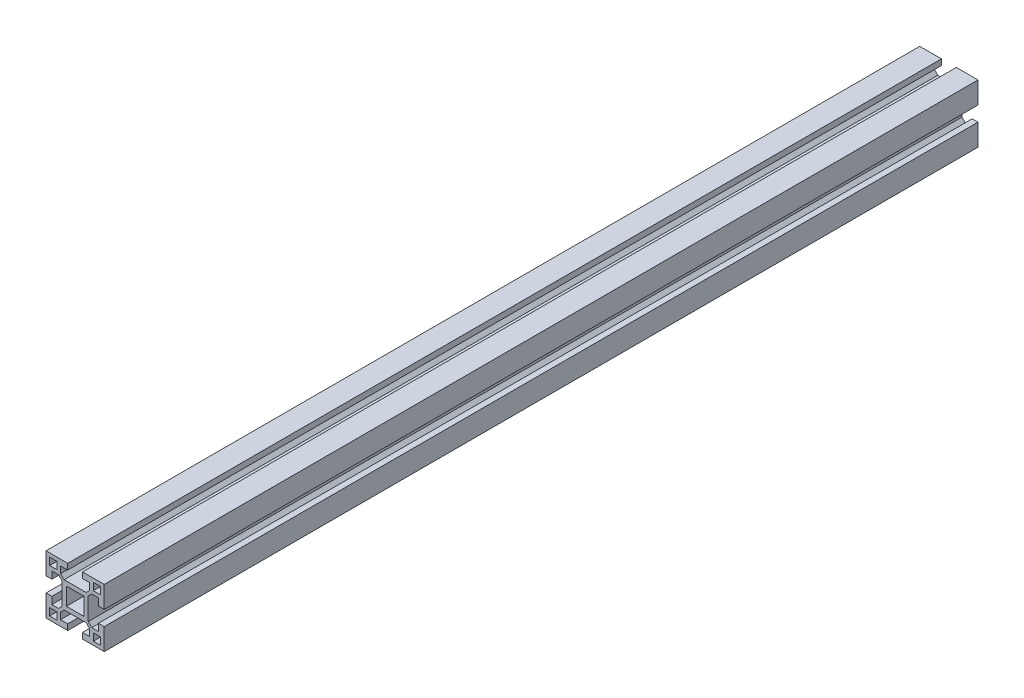
SolidWorks part; units mm, degrees
ref_plane "Plan de face" through (0, 0, 0) normal (0, 0, 1) x (1, 0, 0)
ref_plane "Plan de dessus" through (0, 0, 0) normal (0, 1, 0) x (1, 0, 0)
ref_plane "Plan de droite" through (0, 0, 0) normal (1, 0, 0) x (0, 0, -1)
sketch "Esquisse1" plane through (0, 0, 0) normal (0, 0, 1) x (1, 0, 0)
  line L0 (0, 77.7519) -> (0, -23.3251) construction
  line L1 (17.5, 17.5) -> (12.5, 17.5)
  line L2 (0, 9) -> (7.5858, 9)
  line L3 (0, 6) -> (6, 6)
  line L4 (0, 0) -> (41.9496, 41.9496) construction
  line L5 (7.5858, 9) -> (10, 11.4142)
  line L6 (10, 16) -> (5.1, 16)
  line L7 (5.1, 20) -> (5.1, 16)
  line L8 (12.5, 17.5) -> (12.5, 12.5)
  line L9 (5.1, 20) -> (20, 20)
  line L10 (15, 17.5) -> (15, 15) construction
  line L11 (10, 16) -> (10, 11.4142)
  line L12 (17.5, 15) -> (15, 15) construction
  line L13 (16, 10) -> (11.4142, 10)
  line L14 (20, 5.1) -> (20, 20)
  line L15 (17.5, 12.5) -> (12.5, 12.5)
  line L16 (20, 5.1) -> (16, 5.1)
  line L17 (16, 10) -> (16, 5.1)
  line L18 (9, 7.5858) -> (11.4142, 10)
  line L19 (6, 0) -> (6, 6)
  line L20 (9, 0) -> (9, 7.5858)
  line L21 (17.5, 17.5) -> (17.5, 12.5)
  line L22 (0, -6) -> (6, -6)
  line L23 (0, -9) -> (7.5858, -9)
  line L24 (7.5858, -9) -> (10, -11.4142)
  line L25 (6, 0) -> (6, -6)
  line L26 (9, 0) -> (9, -7.5858)
  line L27 (9, -7.5858) -> (11.4142, -10)
  line L28 (16, -10) -> (11.4142, -10)
  line L29 (16, -10) -> (16, -5.1)
  line L30 (20, -5.1) -> (16, -5.1)
  line L31 (20, -5.1) -> (20, -20)
  line L32 (17.5, -12.5) -> (12.5, -12.5)
  line L33 (17.5, -17.5) -> (17.5, -12.5)
  line L34 (17.5, -17.5) -> (12.5, -17.5)
  line L35 (10, -16) -> (10, -11.4142)
  line L36 (10, -16) -> (5.1, -16)
  line L37 (5.1, -20) -> (5.1, -16)
  line L38 (5.1, -20) -> (20, -20)
  line L39 (12.5, -17.5) -> (12.5, -12.5)
  line L40 (-6, 0) -> (-6, -6)
  line L41 (-9, 0) -> (-9, -7.5858)
  line L42 (-9, -7.5858) -> (-11.4142, -10)
  line L43 (0, -6) -> (-6, -6)
  line L44 (0, -9) -> (-7.5858, -9)
  line L45 (-7.5858, -9) -> (-10, -11.4142)
  line L46 (-10, -16) -> (-10, -11.4142)
  line L47 (-10, -16) -> (-5.1, -16)
  line L48 (-5.1, -20) -> (-5.1, -16)
  line L49 (-5.1, -20) -> (-20, -20)
  line L50 (-12.5, -17.5) -> (-12.5, -12.5)
  line L51 (-17.5, -17.5) -> (-12.5, -17.5)
  line L52 (-17.5, -17.5) -> (-17.5, -12.5)
  line L53 (-16, -10) -> (-11.4142, -10)
  line L54 (-16, -10) -> (-16, -5.1)
  line L55 (-20, -5.1) -> (-16, -5.1)
  line L56 (-20, -5.1) -> (-20, -20)
  line L57 (-17.5, -12.5) -> (-12.5, -12.5)
  line L58 (0, 6) -> (-6, 6)
  line L59 (0, 9) -> (-7.5858, 9)
  line L60 (-7.5858, 9) -> (-10, 11.4142)
  line L61 (-6, 0) -> (-6, 6)
  line L62 (-9, 0) -> (-9, 7.5858)
  line L63 (-9, 7.5858) -> (-11.4142, 10)
  line L64 (-16, 10) -> (-11.4142, 10)
  line L65 (-16, 10) -> (-16, 5.1)
  line L66 (-20, 5.1) -> (-16, 5.1)
  line L67 (-20, 5.1) -> (-20, 20)
  line L68 (-17.5, 12.5) -> (-12.5, 12.5)
  line L69 (-17.5, 17.5) -> (-17.5, 12.5)
  line L70 (-17.5, 17.5) -> (-12.5, 17.5)
  line L71 (-10, 16) -> (-10, 11.4142)
  line L72 (-10, 16) -> (-5.1, 16)
  line L73 (-5.1, 20) -> (-5.1, 16)
  line L74 (-5.1, 20) -> (-20, 20)
  line L75 (-12.5, 17.5) -> (-12.5, 12.5)
  point P0 (0, 0)
  point P6 (0, 0)
  point P93 (0, 0)
  dimension "D1" = 45
  dimension "D2" = 20
  dimension "D3" = 5.1
  dimension "D4" = 11
  dimension "D5" = 4
  dimension "D6" = 1
  dimension "D7" = 3
  dimension "D8" = 5
  dimension "D9" = 15
  dimension "D10" = 2.5
  dimension "D11" = 4
extrude "Boss.-Extru.1" add sketch "Esquisse1" along normal blind 600 contours L73 L74 L67 L66 L65 L64 L63 L62 L41 L42 L53 L54 L55 L56 L49 L48 L47 L46 L45 L44 L23 L24 L35 L36 L37 L38 L31 L30 L29 L28 L27 L26 L20 L18 L13 L17 L16 L14 L9 L7 L6 L11 L5 L2 L59 L60 L71 L72 L40 L61
